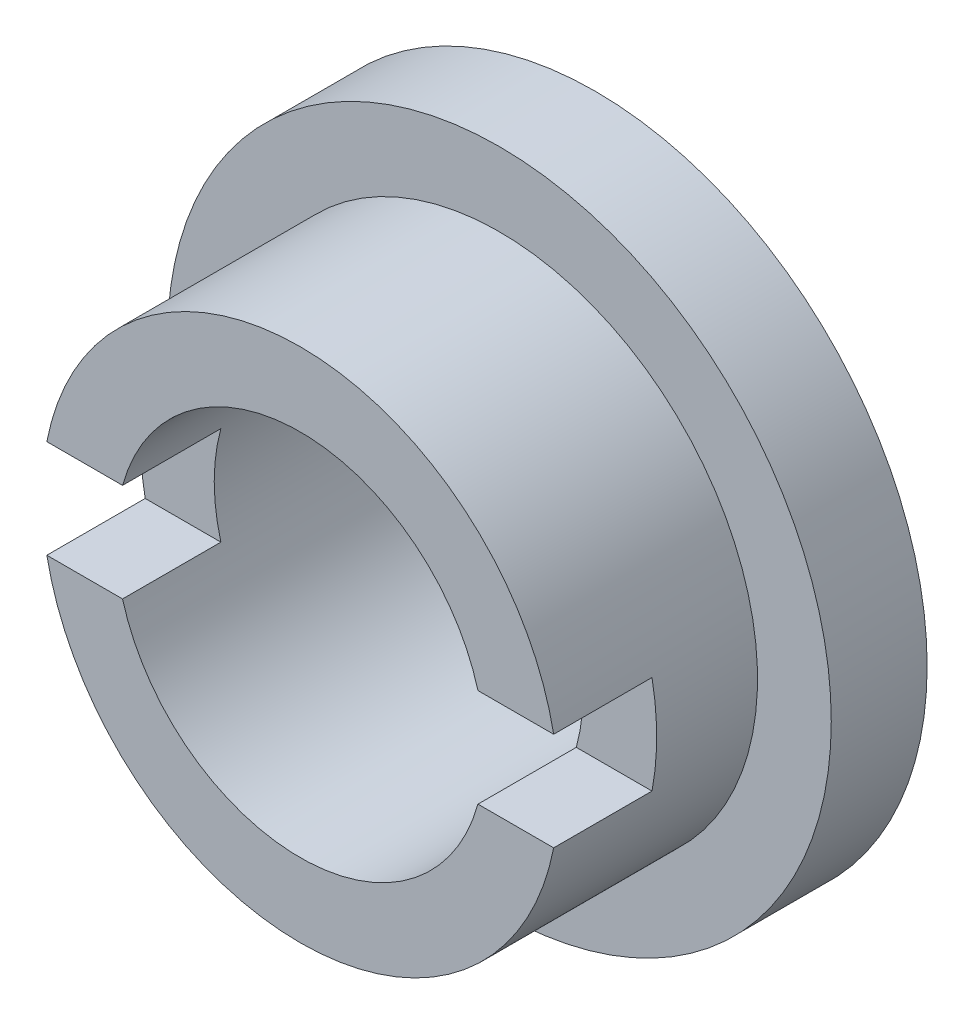
SolidWorks part; units mm, degrees
ref_plane "前视基准面" through (0, 0, 0) normal (0, 0, 1) x (1, 0, 0)
ref_plane "上视基准面" through (0, 0, 0) normal (0, 1, 0) x (1, 0, 0)
ref_plane "右视基准面" through (0, 0, 0) normal (1, 0, 0) x (0, 0, -1)
other "Configuration Table"
sketch "草图1" plane through (0, 0, 0) normal (0, 0, 1) x (1, 0, 0)
  circle A0 centre (0, 0) radius 7.5
  dimension "D1" = 15
extrude "拉伸-薄壁1" add sketch "草图1" along normal blind 12 thin
sketch "草图2" plane through (0, 0, 0) normal (0, 0, -1) x (-1, 0, 0)
  circle A0 centre (0, 0) radius 10.5
extrude "拉伸-薄壁2" add sketch "草图2" against normal blind 3.9 thin
sketch "草图3" plane through (0, 0, 12) normal (0, 0, 1) x (1, 0, 0)
  line L1 (-12.9648, 2) -> (12.9648, 2)
  line L2 (-12.9648, 2) -> (-12.9648, -2)
  line L3 (-12.9648, -2) -> (12.9648, -2)
  line L4 (12.9648, 2) -> (12.9648, -2)
  line L5 (-12.9648, 2) -> (12.9648, -2) construction
  line L6 (-12.9648, -2) -> (12.9648, 2) construction
  point P0 (0, 0)
  dimension "D1" = 4
extrude "切除-拉伸1" cut sketch "草图3" against normal blind 4
